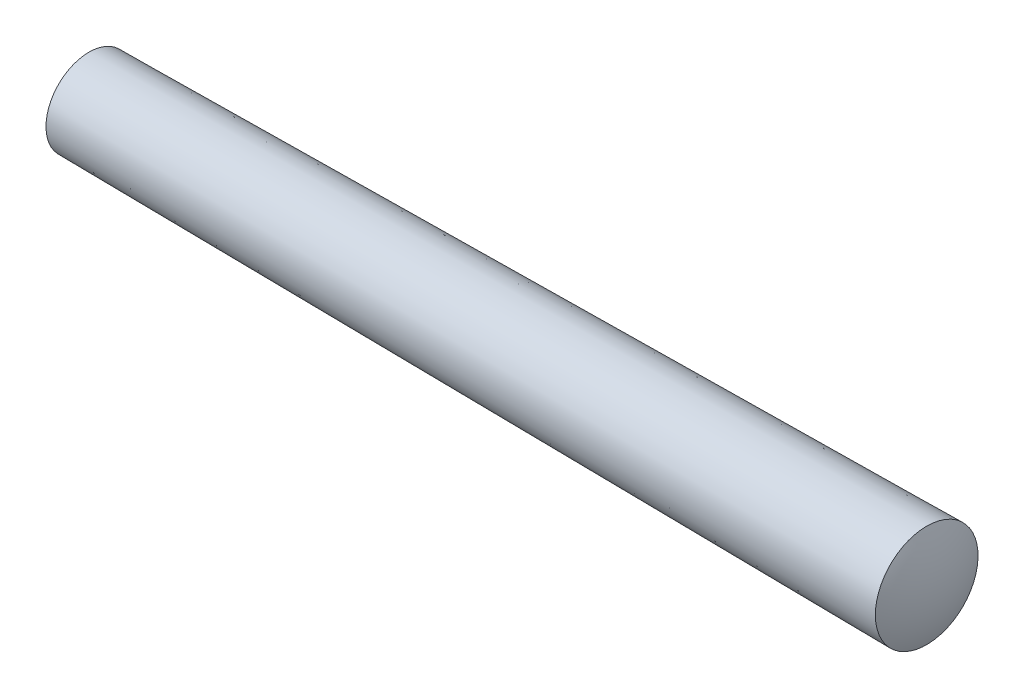
SolidWorks part; units mm, degrees
ref_plane "Plane1" through (0, 0, 0) normal (0, 0, 1) x (1, 0, 0)
ref_plane "Plane2" through (0, 0, 0) normal (0, 1, 0) x (1, 0, 0)
ref_plane "Plane3" through (0, 0, 0) normal (1, 0, 0) x (0, 0, -1)
sketch "Sketch1" plane through (0, 0, 0) normal (0, 0, 1) x (1, 0, 0)
  line L0 (0, 0) -> (210, 0) construction
  line L2 (0.63, 2.5) -> (49.37, 2.9874)
  line L4 (0, 0) -> (50, 0)
  line L5 (0.63, -2.5) -> (49.37, -2.9874) construction
  arc A0 (0.63, 2.5) -> (0, 0) centre (5.2753, 0) ccw
  arc A1 (49.37, 2.9874) -> (50, 0) centre (42.602, 0) cw
  dimension "Diameter" = 5
  dimension "Length" = 50
  dimension "Crown_ht" = 0.63
  dimension "D1" = 0.63
  dimension "D2" = 0.573
revolve "Base-Revolve" add sketch "Sketch1" angle 360 about L0
equation "\"D1@Sketch1\" = \"Crown_ht@Sketch1\""
